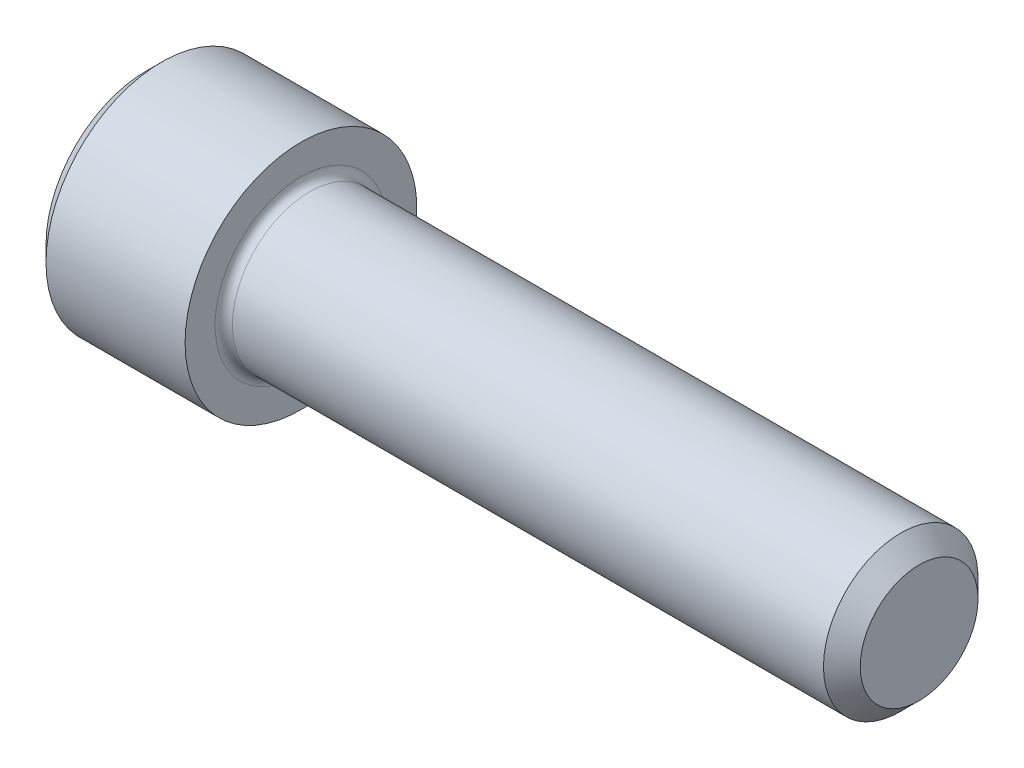
SolidWorks part; units mm, degrees
revolve "Base-Revolve" add sketch "BodySke"
sketch "BodySke" plane through (0, 0, 0) normal (0, 0, 1) x (1, 0, 0)
  line L0 (0, 0) -> (0, 4.1275)
  line L1 (0.635, 4.7625) -> (6.35, 4.7625)
  line L2 (6.35, 4.7625) -> (6.35, 3.175)
  line L3 (6.35, 3.175) -> (30.9943, 3.175)
  line L4 (31.75, 2.4193) -> (31.75, 0)
  line L5 (31.75, 0) -> (0, 0)
  line L6 (-31.75, 0) -> (127, 0) construction
  line L7 (0, 4.1275) -> (0.635, 4.7625)
  line L8 (31.75, 2.4193) -> (30.9943, 3.175)
  line L9 (0, -4.1275) -> (0.635, -4.7625) construction
  line L10 (31.75, -2.4193) -> (30.9943, -3.175) construction
  line L11 (7.62, 9.525) -> (7.62, 3.175) construction
  line L12 (6.35, 9.525) -> (6.35, 3.175) construction
  line L13 (-6.35, 9.525) -> (-6.35, 3.175) construction
  dimension "Diameter" = 6.35
  dimension "Head_ht" = 6.35
  dimension "Length" = 25.4
  dimension "Body_ch_ang" = 45
  dimension "Head_dia" = 9.525
  dimension "Head_ch_ang" = 45
  dimension "Head_side_ht" = 5.715
  dimension "Minor_dia" = 4.8387
  dimension "Advance" = 1.27
  dimension "Thread_nom" = 25.4
  dimension "Thread_length" = 38.1
cosmetic thread "ThreadCosmetic"
fillet "Fillet1" radius 0.3556 1 edges at (6.35, 0, 3.175)
ref_plane "Plane1" through (0, 0, 0) normal (0, 0, 1) x (1, 0, 0)
ref_plane "Plane2" through (0, 0, 0) normal (0, 1, 0) x (1, 0, 0)
ref_plane "Plane3" through (0, 0, 0) normal (1, 0, 0) x (0, 0, -1)
sketch "Sketch2" plane through (0, 0, 0) normal (0, 0, 1) x (1, 0, 0)
  line L0 (0, 2.3813) -> (3.048, 2.3812)
  line L1 (3.048, 2.3812) -> (4.4228, 0)
  line L2 (-31.75, 0) -> (127, 0) construction
  line L3 (4.4228, 0) -> (0, 0)
  line L4 (0, 0) -> (0, 2.3813)
  line L5 (0, 4.1275) -> (0, -4.1275) construction
  line L6 (0, 0) -> (47.625, 0) construction
  line L7 (6.35, -4.7625) -> (6.35, 4.7625) construction
  dimension "D1" = 2.3813
  dimension "D2" = 60
revolve "Hex-PreBroach" cut sketch "Sketch2" angle 360 about L6
sketch "Sketch3" plane through (0, 0, 0) normal (-1, 0, 0) x (0, 0.5, 0.866)
  line L0 (1.3748, 2.3813) -> (-1.3748, 2.3813)
  line L1 (-1.3748, 2.3813) -> (-2.7496, 0)
  line L2 (1.3748, 2.3813) -> (2.7496, 0)
  line L3 (1.3748, -2.3812) -> (2.7496, 0)
  line L4 (1.3748, -2.3812) -> (-1.3748, -2.3812)
  line L5 (-1.3748, -2.3812) -> (-2.7496, 0)
  dimension "D1" = 2.3813
  dimension "D2" = 2.3813
  dimension "Hex_size" = 4.7625
extrude "Hex" cut sketch "Sketch3" against normal blind 3.048
sketch "Sketch4" plane through (0, 0, 0) normal (-1, 0, 0) x (0, 0, 1)
  line L0 (0, 0) -> (2.8067, 0)
  line L1 (0, 0) -> (6.1484, 3.5498) construction
  line L2 (0, 0) -> (1.4033, 2.4307)
  line L3 (2.3336, 0.614) -> (2.6851, 0.817)
  line L4 (1.6986, 1.7139) -> (2.0501, 1.9169)
  arc A0 (2.3336, 0.614) -> (1.6986, 1.7139) centre (0, 0) ccw
  arc A1 (2.8067, 0) -> (2.6851, 0.817) centre (0, 0) ccw
  arc A2 (1.4033, 2.4307) -> (2.0501, 1.9169) centre (0, 0) cw
  dimension "D1" = 30
  dimension "D2" = 60
  dimension "Spline_p_dim" = 1.27
  dimension "D3" = 0.635
extrude "Spline" [suppressed] cut sketch "Sketch4" against normal blind 3.048
pattern_circular "CirPattern1" [suppressed] count 6 every 60
sketch "Sketch5" plane through (0, 0, 0) normal (0, 0, 1) x (1, 0, 0)
  line L0 (-31.75, 0) -> (127, 0) construction
  line L2 (0, 4.1275) -> (0, -4.1275) construction
  circle A0 centre (2.159, 0) radius 0.5905
  dimension "Drilled_hole_dia" = 1.1811
  dimension "Drilled_hole_loc" = 2.159
extrude "Hole" [suppressed] cut sketch "Sketch5" against normal through all and the other way through all
pattern_circular "Drilled-4" [suppressed] count 2 every 60
pattern_circular "Drilled-6" [suppressed] count 3 every 60
sketch "ThdSchSke" plane through (0, 0, 0) normal (0, 0, 1) x (1, 0, 0)
  line L0 (7.62, -2.4193) -> (7.0909, -3.175)
  line L1 (7.62, -2.4193) -> (8.1491, -3.175)
  line L2 (8.1491, -3.175) -> (8.1491, -3.9688)
  line L3 (-3.175, 0) -> (5.1513, 0) construction
  line L5 (8.1491, -3.9688) -> (7.0909, -3.9688)
  line L6 (7.0909, -3.9688) -> (7.0909, -3.175)
  line L7 (0, 4.1275) -> (0, -4.1275) construction
  dimension "Thread_minor" = 4.8387
  dimension "Diameter" = 6.35
  dimension "Start" = 7.62
revolve "ThreadSchematic" [suppressed] cut sketch "ThdSchSke" angle 360 about L3
pattern_linear "ThdSchPat" [suppressed]
equation "\"D2@Sketch3\" = \"Hex_size@Sketch3\" / 2"
equation "\"D1@Sketch3\" = \"Hex_size@Sketch3\" / 2"
equation "\"D1@Sketch2\" = \"Hex_size@Sketch3\" / 2"
equation "\"D3@Sketch4\" = \"Spline_p_dim@Sketch4\" / 2"
equation "\"Thread_minor@ThreadCosmetic\"  =  \"Minor_dia@BodySke\""
equation "\"D2@CirPattern1\" = 360 / \"Num_teeth@CirPattern1\""
equation "\"Wall_thickness@Sketch2\" = \"Head_ht@BodySke\" - \"Key_eng@Hex\""
equation "\"Thread_length@ThreadCosmetic\" = ((sgn( (\"Length@BodySke\" - \"Advance@BodySke\" ) - \"Thread_nom@BodySke\" )-1)*( (\"Length@BodySke\" - \"Advance@BodySke\" ) - \"Thread_nom@BodySke\" ))/-2+ \"Thread_nom@BodySke\""
equation "\"Thread_minor@ThdSchSke\" = \"Minor_dia@BodySke\""
equation "\"Diameter@ThdSchSke\" = \"Diameter@BodySke\""
equation "\"Overcut@ThdSchSke\" = \"Diameter@BodySke\" * 1.25"
equation "\"Start@ThdSchSke\" = \"Head_ht@BodySke\" + \"Length@BodySke\" - \"Thread_length@ThreadCosmetic\"  '---Non-countersunk---"
equation "\"Num_threads@ThdSchPat\" = int( \"Thread_length@ThreadCosmetic\" / \"Advance@BodySke\" + 0.999 )  + 1"
equation "\"Advance@ThdSchPat\" = \"Thread_length@ThreadCosmetic\" /  (\"Num_threads@ThdSchPat\" - 1) 'relax it"
equation "\"Num_threads@ThdSchPat\" = \"Num_threads@ThdSchPat\" - sgn( \"Num_threads@ThdSchPat\" - 1) '---chamfered tips only---"
